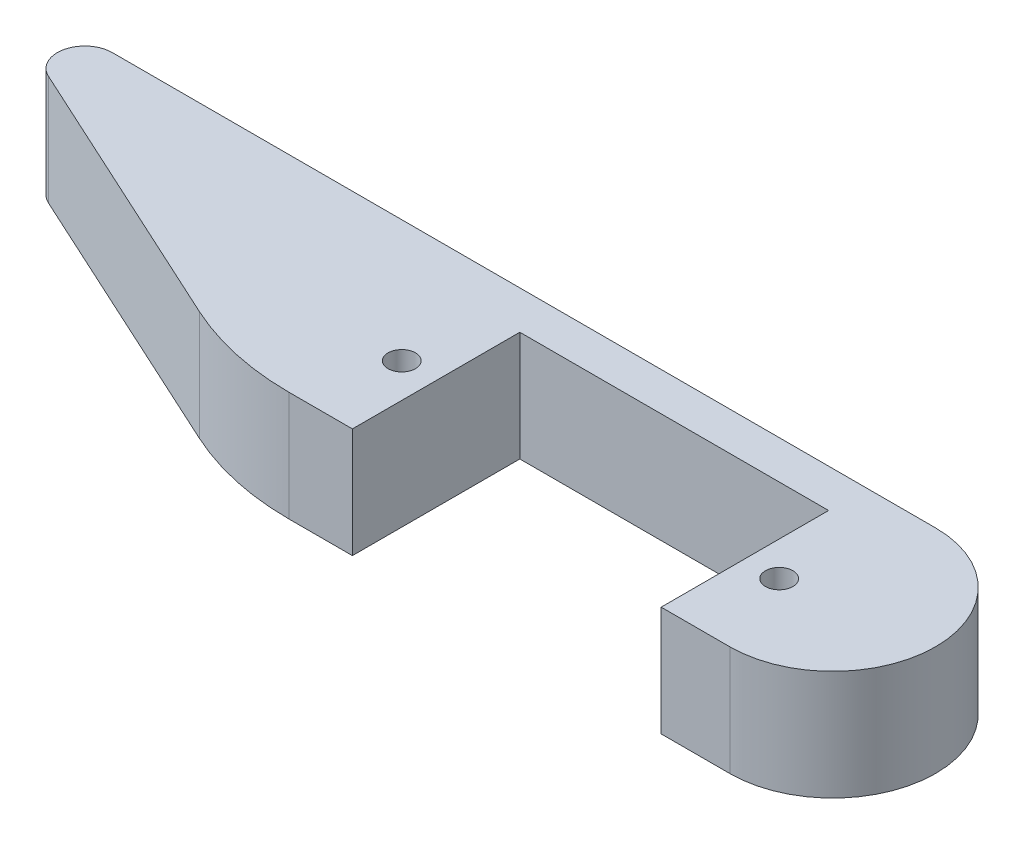
SolidWorks part; units mm, degrees
ref_plane "前基準面" through (0, 0, 0) normal (0, 0, 1) x (1, 0, 0)
ref_plane "上基準面" through (0, 0, 0) normal (0, 1, 0) x (1, 0, 0)
ref_plane "右基準面" through (0, 0, 0) normal (1, 0, 0) x (0, 0, -1)
sketch "草圖1" plane through (0, 0, 0) normal (0, 1, 0) x (1, 0, 0)
  line L0 (0, 0) -> (0, 12.2)
  line L1 (0, 12.2) -> (-22.5, 12.2)
  line L2 (-22.5, 12.2) -> (-22.5, 0)
  line L3 (5, 15) -> (-55, 15)
  line L4 (-55.8351, 11.1827) -> (-35.4752, 1.8269)
  line L5 (-27.1243, 0) -> (-22.5, 0)
  line L6 (5, 0) -> (0, 0)
  line L7 (-22.5, 12.2) -> (0, 0) construction
  line L8 (-25, 6.1) -> (2.5, 6.1) construction
  line L9 (-11.25, 6.1) -> (-22.5, 0) construction
  arc A0 (5, 0) -> (5, 15) centre (5, 7.5) ccw
  arc A1 (-55, 15) -> (-55.8351, 11.1827) centre (-55, 13) ccw
  arc A2 (-35.4752, 1.8269) -> (-27.1243, 0) centre (-27.1243, 20) ccw
  circle A3 centre (-25, 6.1) radius 1
  circle A4 centre (2.5, 6.1) radius 1
  dimension "D3" = 20
  dimension "D4" = 2
  dimension "D6" = 7.5
  dimension "D9" = 2
  dimension "D1" = 22.5
  dimension "D2" = 12.2
  dimension "D5" = 5
  dimension "D7" = 60
  dimension "D8" = 27.5
extrude "填料-伸長1" add sketch "草圖1" along normal blind 8
